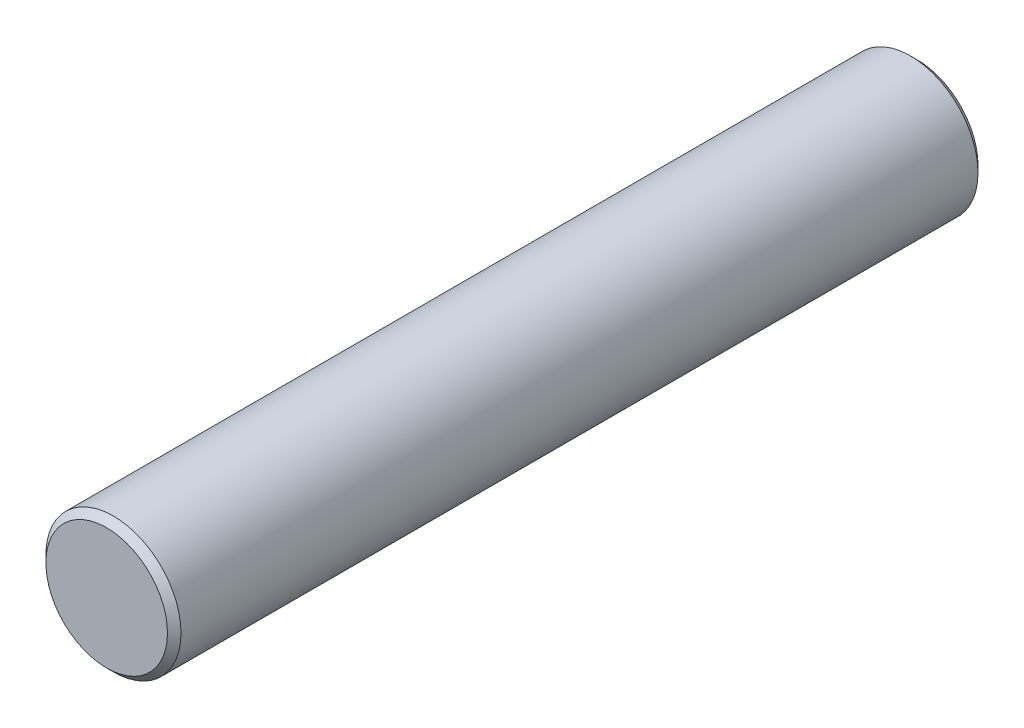
SolidWorks part; units mm, degrees
ref_plane "Plan de face" through (0, 0, 0) normal (0, 0, 1) x (1, 0, 0)
ref_plane "Plan de dessus" through (0, 0, 0) normal (0, 1, 0) x (1, 0, 0)
ref_plane "Plan de droite" through (0, 0, 0) normal (1, 0, 0) x (0, 0, -1)
sketch "Esquisse1" plane through (0, 0, 0) normal (0, 0, 1) x (1, 0, 0)
  circle A0 centre (0, 0) radius 5
  dimension "D1" = 10
extrude "Boss.-Extru.1" add sketch "Esquisse1" along normal blind 60
chamfer "Chanfrein1" distance 0.5 angle 45 2 edges at (5, 0, 0) (5, 0, 60)
